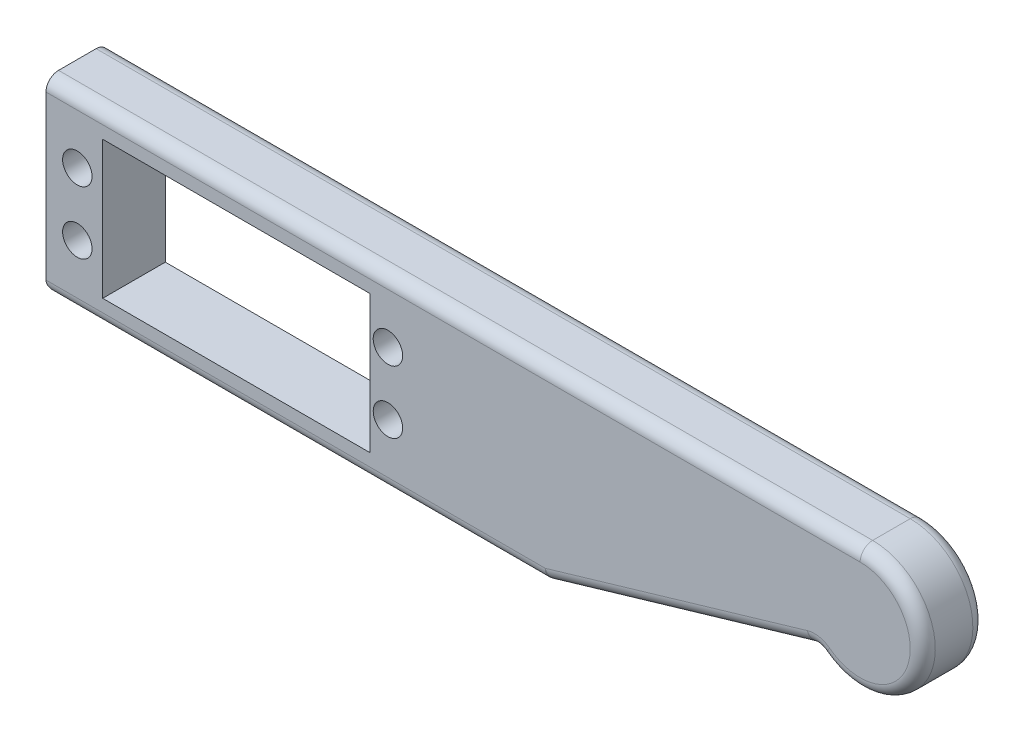
SolidWorks part; units mm, degrees
ref_plane "Front Plane" through (0, 0, 0) normal (0, 0, 1) x (1, 0, 0)
ref_plane "Top Plane" through (0, 0, 0) normal (0, 1, 0) x (1, 0, 0)
ref_plane "Right Plane" through (0, 0, 0) normal (1, 0, 0) x (0, 0, -1)
sketch "Sketch1" plane through (0, 0, 0) normal (0, 0, 1) x (1, 0, 0)
  line L0 (-70, 0) -> (70, 0) construction
  line L1 (-70, 15) -> (60, 15)
  line L2 (-70, 15) -> (-70, -15)
  line L4 (-65, 5) -> (-65, -5) construction
  line L5 (-65, 5) -> (-15.4, 5) construction
  line L6 (-60.95, 11) -> (-19.45, 11)
  line L7 (-60.95, 11) -> (-60.95, -11)
  line L8 (-60.95, -11) -> (-19.45, -11)
  line L9 (-19.45, 11) -> (-19.45, -11)
  line L10 (-60.95, 11) -> (-19.45, -11) construction
  line L11 (-60.95, -11) -> (-19.45, 11) construction
  line L12 (-70, -15) -> (10, -15)
  line L14 (10, -15) -> (53.1727, -2.3067)
  circle A1 centre (-65, 5) radius 2.35
  circle A2 centre (-15.4, 5) radius 2.35
  circle A3 centre (-15.4, -5) radius 2.35
  circle A4 centre (-65, -5) radius 2.35
  arc A5 (53.1727, -2.3067) -> (60, 15) centre (60, 5) ccw
  point P11 (-65, 0)
  point P16 (-40.2, 0)
  point P24 (-40.2, 5)
  dimension "D3" = 80
  dimension "D1" = 10
  dimension "D4" = 4.7
  dimension "D5" = 49.6
  dimension "D7" = 10
  dimension "D11" = 140
  dimension "D2" = 30
  dimension "D6" = 5
  dimension "D8" = 41.5
  dimension "D9" = 22
  dimension "D10" = 130
  dimension "D12" = 45
extrude "Boss-Extrude1" add sketch "Sketch1" along normal blind 10
fillet "Fillet1" radius 2 11 edges at (-5, 15, 10) (-5, 15, 0) (69.3023, 1.3303, 10) (69.3023, 1.3303, 0) (31.5863, -8.6533, 10) (53.1727, -2.3067, 5) (31.5863, -8.6533, 0) (-70, -15, 5) (-30, -15, 10) (10, -15, 5) (-30, -15, 0)
chamfer "Chamfer1" distance 2 angle 30 1 edges at (-19.45, 0, 10)
